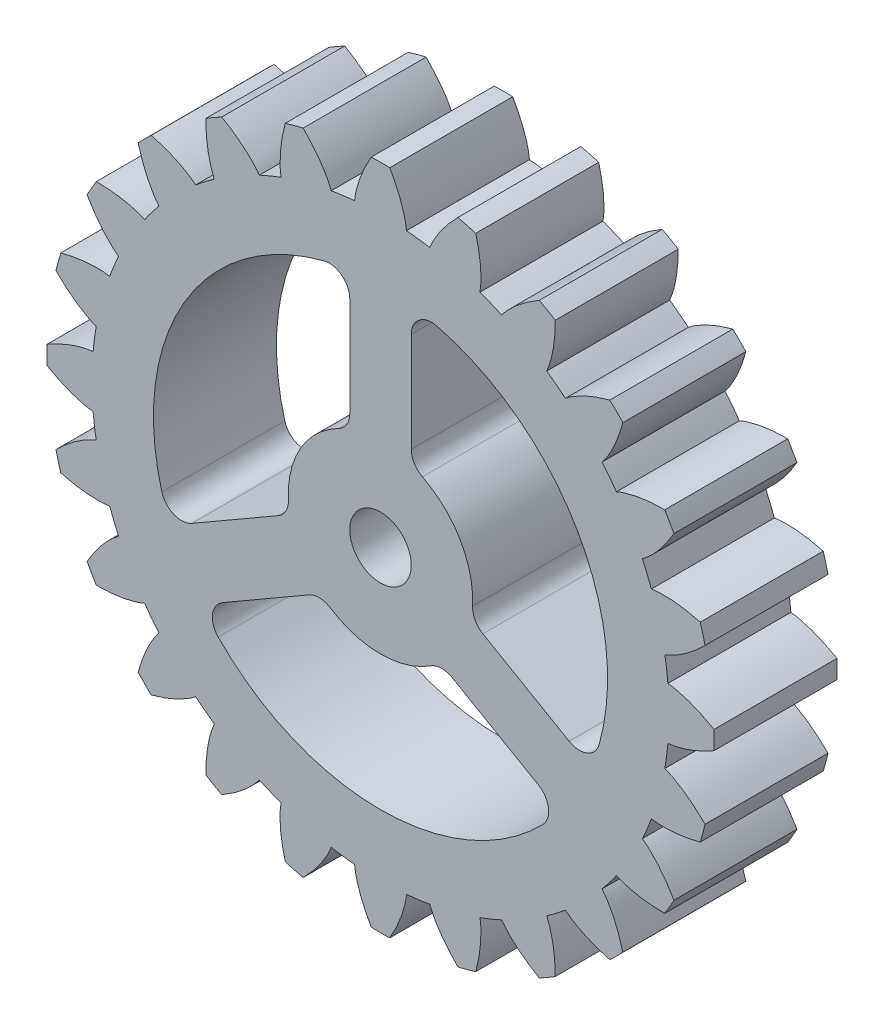
SolidWorks part; units mm, degrees
material "ABS"
ref_plane "Front Plane" through (0, 0, 0) normal (0, 0, 1) x (1, 0, 0)
ref_plane "Top Plane" through (0, 0, 0) normal (0, 1, 0) x (1, 0, 0)
ref_plane "Right Plane" through (0, 0, 0) normal (1, 0, 0) x (0, 0, -1)
sketch "Definition Drawing" plane through (0, 0, 0) normal (0, 0, 1) x (1, 0, 0)
  line L0 (16.2789, 0) -> (14.2789, 0) construction
  line L1 (0, 0) -> (-6.9516, 11.976) construction
  line L2 (0, 0) -> (0, 16.2789) construction
  line L3 (0, 0) -> (1.2743, 13.7886) construction
  line L4 (-6.9516, 11.976) -> (0.4506, 16.2726) construction
  line L5 (0, 0) -> (0.9494, 15.2493) construction
  line L6 (0, 0) -> (0.9993, 15.2462) construction
  line L7 (0, 0) -> (-5.0256, 12.9032) construction
  line L8 (-5.0256, 12.9032) -> (0.9558, 15.2329) construction
  line L9 (0, 0) -> (-2.9798, 13.5229) construction
  line L10 (-2.9798, 13.5229) -> (1.1993, 14.4438) construction
  line L11 (0, 0) -> (-0.8631, 13.8204) construction
  line L12 (-0.8631, 13.8204) -> (1.2725, 13.9538) construction
  circle A0 centre (0, 0) radius 13.8474 construction
  circle A1 centre (0, 0) radius 14.2789 construction
  circle A2 centre (0, 0) radius 15.2789 construction
  circle A3 centre (0, 0) radius 16.2789 construction
  circle A4 centre (0, 0) radius 14.0789 construction
  arc A5 (0.9494, 15.2493) -> (0.9993, 15.2462) centre (0, 0) cw construction
  spline S0 degree 3 poles (1.2743, 13.7886) (1.2817, 14.0092) (1.1458, 14.8862) (0.7794, 15.701) (0.4506, 16.2726) knots 0 0 0 0 0.250019 1 1 1 1 construction
  point P13 (15.2789, 0)
  dimension "D4" = 30.5577
  dimension "D5" = 27.6947
  dimension "D1" = 2
  dimension "D2" = 0.2
  dimension "D3" = 3.75
  dimension "D6" = 0.05
  dimension "D7" = 35.413
  dimension "D11" = 6.4191
  dimension "D12" = 4.2794
  dimension "D13" = 2.1397
  dimension "D8" = 26.56
  dimension "D9" = 17.707
  dimension "D10" = 8.853
sketch "Sketch5" plane through (0, 0, 0) normal (0, 0, 1) x (1, 0, 0)
  circle A1 centre (0, 0) radius 14.0789
  circle A2 centre (0, 0) radius 1.5
  circle A3 centre (0, 0) radius 14.0789 construction
  dimension "D1" = 3
extrude "Extrude Body" add sketch "Sketch5" along normal mid plane 6
sketch "Sketch6" plane through (0, 0, 0) normal (0, 0, 1) x (1, 0, 0)
  line L0 (0, 16.2789) -> (0, 0) construction
  line L4 (1.2743, 13.7886) -> (0.138, 1.4936)
  line L5 (0, 0) -> (1.2743, 13.7886) construction
  line L6 (-1.2743, 13.7886) -> (-0.138, 1.4936)
  arc A0 (0.4506, 16.2726) -> (-0.4506, 16.2726) centre (0, 0) ccw
  arc A3 (0.138, 1.4936) -> (-0.138, 1.4936) centre (0, 0) ccw
  circle A4 centre (0, 0) radius 1.5 construction
  spline S0 degree 3 poles (1.2743, 13.7886) (1.2817, 14.0092) (1.1458, 14.8862) (0.7794, 15.701) (0.4506, 16.2726) knots 0 0 0 0 0.250019 1 1 1 1
  spline S1 degree 3 poles (-1.2743, 13.7886) (-1.2817, 14.0092) (-1.1458, 14.8862) (-0.7794, 15.701) (-0.4506, 16.2726) knots 0 0 0 0 0.250019 1 1 1 1
extrude "Extrude Tooth" add sketch "Sketch6" along normal mid plane 6
pattern_circular "CirPattern1" count 24 over 360 about axis through (0, 0, 3) along (0, 0, -1) of "Extrude Tooth"
sketch "Sketch8" plane through (0, 0, 0) normal (0, 0, 1) x (1, 0, 0)
  line L6 (0, 16.2789) -> (0, 0) construction
  line L7 (0, 0) -> (14.0979, -8.1394) construction
  line L8 (1.5, 9.7639) -> (1.5, 4.899)
  line L9 (4.9926, -1.1505) -> (9.2058, -3.5829)
  circle A2 centre (0, 0) radius 16.2789 construction
  arc A20 (10.6688, -2.9864) -> (2.748, 10.7326) centre (0, 0) ccw
  circle A21 centre (0, 0) radius 14.0789 construction
  arc A23 (9.2058, -3.5829) -> (10.6688, -2.9864) centre (9.7058, -2.7169) ccw
  arc A24 (4.9926, -1.1505) -> (4.494, -0.2327) centre (5.4926, -0.2844) cw
  arc A25 (1.5, 4.899) -> (2.0455, 4.0083) centre (2.5, 4.899) ccw
  arc A26 (1.5, 9.7639) -> (2.748, 10.7326) centre (2.5, 9.7639) cw
  arc A27 (4.494, -0.2327) -> (2.0455, 4.0083) centre (0, 0) ccw
  circle A28 centre (0, 0) radius 1.5 construction
  dimension "D1" = 3
  dimension "D6" = 1
  dimension "D4" = 3
  dimension "D5" = 3
  dimension "D2" = 3
  dimension "D3" = 120
extrude "Cut Spoke" cut sketch "Sketch8" against normal through all and the other way through all
pattern_circular "Pattern Spokes" count 3 over 360 about axis through (0, 0, 0) along (0, 0, 1) of "Cut Spoke"
equation "\"nTeeth\"= 24"
equation "\"xThickness\"= 6"
equation "\"dShaft\"= 3"
equation "\"aPressure\"=25"
equation "\"pitch\"= 4"
equation "\"rHeight\"= 2"
equation "\"rClearance\"= 0.2"
equation "\"xClearance\"=0.05"
equation "\"rFillet\"= 1"
equation "\"nSpokes\"= int ( ( \"nTeeth\" - 1 ) / 10 ) + 1'rounds up"
equation "\"dPitch\"= \"nTeeth\" * \"pitch\" / pi"
equation "\"xWall\"= IIF ( \"nTeeth\" > 30 , \"nTeeth\" / 10 , 3 )"
equation "\"dBase\"= \"dPitch\" * cos ( \"aPressure\" )"
equation "\"rOuter\"= \"dPitch\" / 2 + \"rHeight\" / 2"
equation "\"xInvolute\"= sqr ( \"rOuter\" ^ 2 - ( \"dBase\" / 2 ) ^ 2 )"
equation "\"aInvolute\"= 360 * \"xInvolute\" / ( \"dBase\" / 2 ) / 2 / pi"
equation "\"D1@Definition Drawing\" = \"rHeight\""
equation "\"D2@Definition Drawing\" = \"rClearance\""
equation "\"D4@Definition Drawing\" = \"dPitch\""
equation "\"D6@Definition Drawing\" = \"xClearance\""
equation "\"D5@Definition Drawing\" = \"dBase\""
equation "\"D7@Definition Drawing\" = \"aInvolute\""
equation "\"D11@Definition Drawing\" = \"xInvolute\" * 0.75"
equation "\"D12@Definition Drawing\" = \"xInvolute\" * 0.5"
equation "\"D13@Definition Drawing\" = \"xInvolute\" * 0.25"
equation "\"D8@Definition Drawing\" = \"aInvolute\" * 0.75"
equation "\"D9@Definition Drawing\" = \"aInvolute\" * 0.5"
equation "\"D10@Definition Drawing\" = \"aInvolute\" * 0.25"
equation "\"D1@Extrude Body\"=\"xThickness\""
equation "\"D1@Sketch5\"=\"dShaft\""
equation "\"D3@Definition Drawing\" = 360 / \"nTeeth\" / 2 / 2"
equation "\"D5@Sketch8\"=\"xWall\""
equation "\"D1@Sketch8\"=\"xWall\""
equation "\"D4@Sketch8\"=\"xWall\""
equation "\"D6@Sketch8\"=\"rFillet\""
equation "\"D1@Pattern Spokes\" = \"nSpokes\""
equation "\"rHub\"= IIF ( \"xWall\" * \"nSpokes\" / 6 > \"xWall\" , \"xWall\" * \"nSpokes\" / 6 , \"xWall\" )"
equation "\"D2@Sketch8\"=\"rHub\""
equation "\"D3@Sketch8\"=360/\"nSpokes\""
equation "\"D1@Extrude Tooth\" = \"xThickness\""
equation "\"D1@CirPattern1\"=\"nTeeth\""
